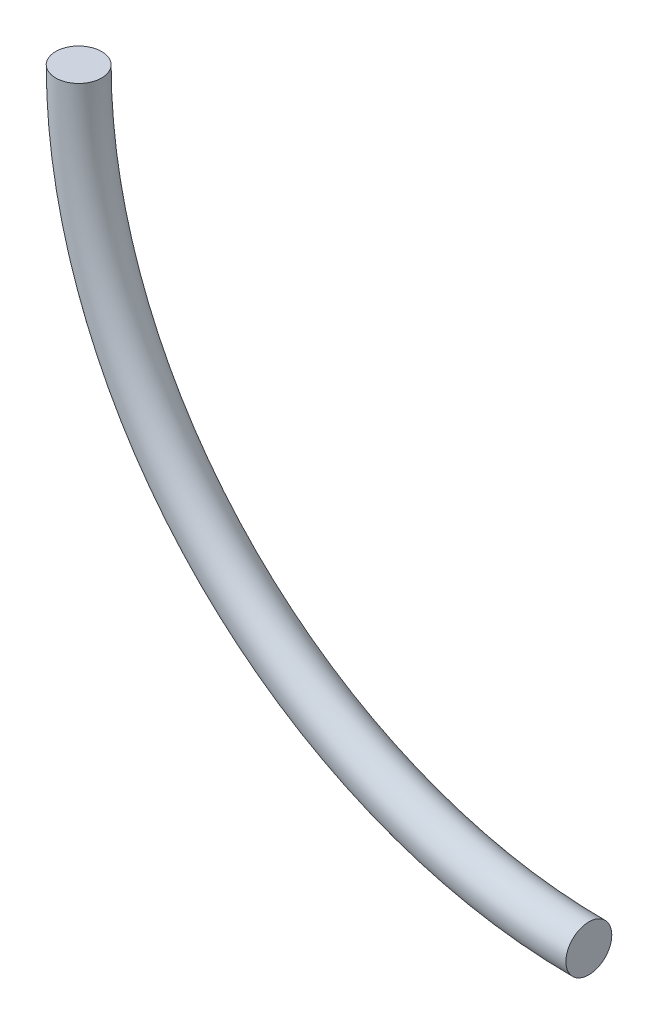
SolidWorks part; units mm, degrees
material "Polyurethane"
ref_plane "Plan de face" through (0, 0, 0) normal (0, 0, 1) x (1, 0, 0)
ref_plane "Plan de dessus" through (0, 0, 0) normal (0, 1, 0) x (1, 0, 0)
ref_plane "Plan de droite" through (0, 0, 0) normal (1, 0, 0) x (0, 0, -1)
sketch "Sketch1" plane through (0, 0, 0) normal (0, 0, 1) x (1, 0, 0)
  line L0 (0, 0) -> (50, 0) construction
  line L1 (50, 0) -> (50, -50) construction
  arc A0 (0, 0) -> (50, -50) centre (50, 0) ccw
  dimension "D1" = 50
sketch "Sketch2" plane through (0, 0, 0) normal (0, 1, 0) x (1, 0, 0)
  circle A0 centre (0, 0) radius 2.25
  dimension "D1" = 4.5
sweep "Sweep1" add profiles "Sketch2" path "Sketch1"
